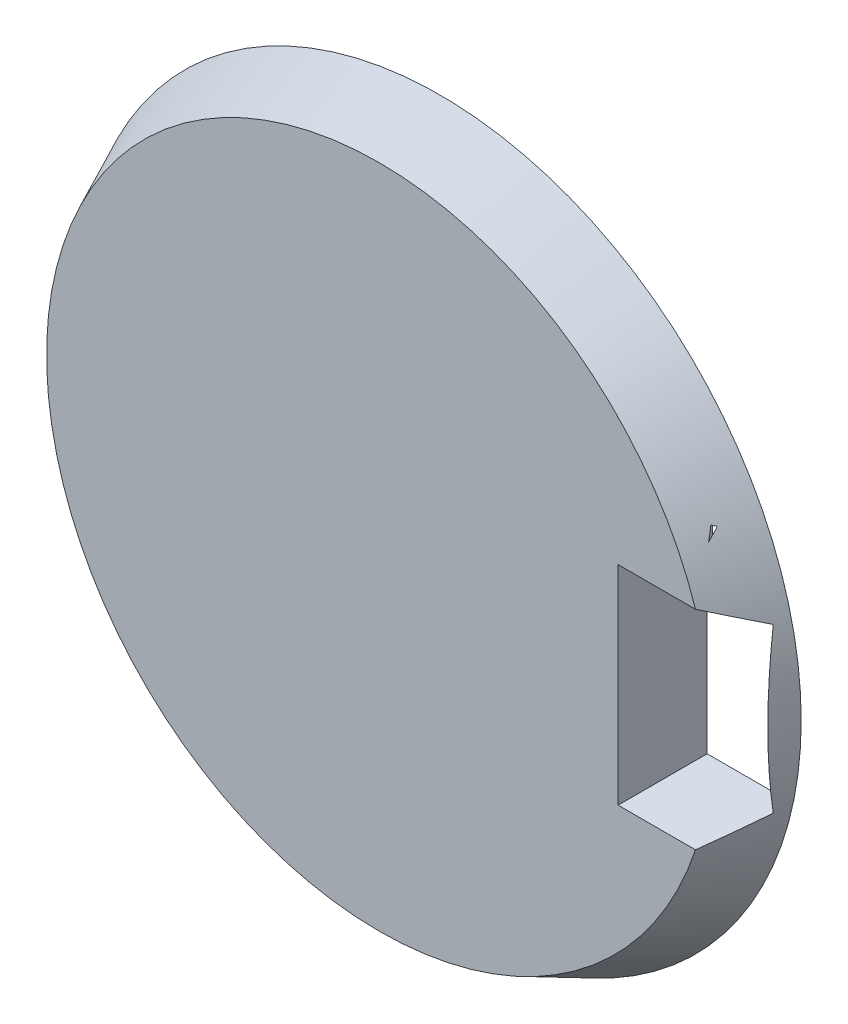
SolidWorks part; units mm, degrees
material "ABS PC"
ref_plane "Front Plane" through (0, 0, 0) normal (0, 0, 1) x (1, 0, 0)
ref_plane "Top Plane" through (0, 0, 0) normal (0, 1, 0) x (1, 0, 0)
ref_plane "Right Plane" through (0, 0, 0) normal (1, 0, 0) x (0, 0, -1)
sketch "Sketch1" plane through (0, 0, 0) normal (0, 0, 1) x (1, 0, 0)
  line L0 (0, 0) -> (0, 6.3935) construction
  line L1 (0, 6.3935) -> (0, 0) construction
  line L2 (0, 0) -> (10, 0) construction
  line L4 (8.8, 2.5) -> (11.2, 2.5)
  line L5 (8.8, 2.5) -> (8.8, -2.5)
  line L6 (8.8, -2.5) -> (11.2, -2.5)
  line L7 (11.2, 2.5) -> (11.2, -2.5)
  line L8 (8.8, 2.5) -> (11.2, -2.5) construction
  line L9 (8.8, -2.5) -> (11.2, 2.5) construction
  circle A0 centre (0, 0) radius 11.9
  dimension "D1" = 10
  dimension "D4" = 23.8
  dimension "D2" = 5
  dimension "D3" = 2.4
extrude "Boss-Extrude2" add sketch "Sketch1" along normal blind 2 draft 25
sketch "Sketch2" plane through (0, 0, 2) normal (0, 0, 1) x (1, 0, 0)
  line L0 (0, 0) -> (-10, 0) construction
  line L1 (-10, 0) -> (-10, -1.2) construction
  line L7 (-11.15, -2.4) -> (-8.85, 0) construction
  line L8 (-11.0714, 0.3126) -> (-9.15, -2.4) construction
  line L9 (-11.05, 1.1) -> (-8.95, 1.1)
  line L10 (-11.05, 1.1) -> (-11.05, -1.1)
  line L11 (-11.05, -1.1) -> (-8.95, -1.1)
  line L12 (-8.95, 1.1) -> (-8.95, -1.1)
  line L13 (-11.05, 1.1) -> (-8.95, -1.1) construction
  line L14 (-11.05, -1.1) -> (-8.95, 1.1) construction
  dimension "D1" = 10
  dimension "D2" = 1.2
  dimension "D3" = 2
  dimension "D4" = 2.1
  dimension "D5" = 2.2
sketch "Sketch3" plane through (0, 2.0535, -0.9576) normal (0, -0.9063, 0.4226) x (1, 0, 0)
  line L0 (9.1419, 3.2633) -> (10, 1.0565)
  line L1 (10.4164, 3.2633) -> (7.8674, 3.2633) construction
  line L2 (11.2, 1.0565) -> (8.8, 1.0565) construction
sketch "Sketch4" plane through (0, 2.0535, -0.9576) normal (0, -0.9063, 0.4226) x (1, 0, 0)
  line L0 (9.1419, 3.2633) -> (10, 1.0565) construction
  line L1 (8.9711, 3.2633) -> (10.1708, 3.2633)
  line L2 (8.9711, 3.2633) -> (8.9711, 1.0565)
  line L3 (8.9711, 1.0565) -> (10.1708, 1.0565)
  line L4 (10.1708, 3.2633) -> (10.1708, 1.0565)
  line L5 (8.9711, 3.2633) -> (10.1708, 1.0565) construction
  line L6 (8.9711, 1.0565) -> (10.1708, 3.2633) construction
  line L7 (11.2, 1.0565) -> (8.8, 1.0565) construction
  point P0 (9.5709, 2.1599)
extrude "Cut-Extrude1" cut sketch "Sketch4" against normal blind 2
sketch "Sketch6" plane through (0, 0, 2) normal (0, 0, 1) x (1, 0, 0)
